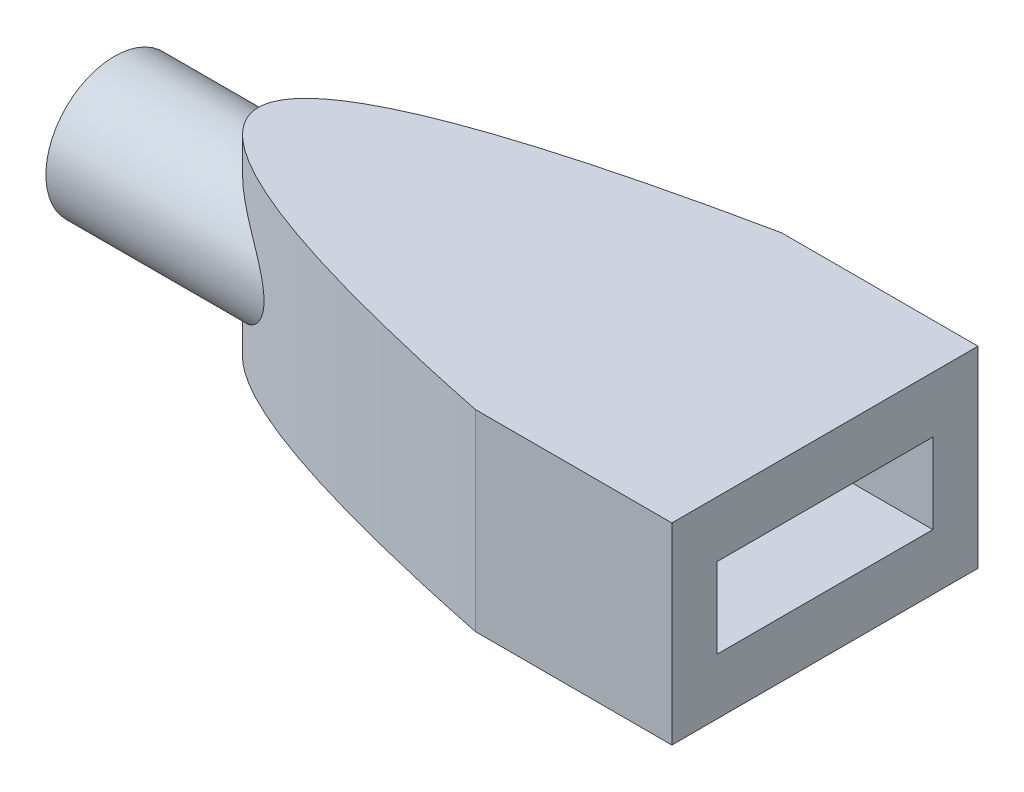
SolidWorks part; units mm, degrees
ref_plane "Front Plane" through (0, 0, 0) normal (0, 0, 1) x (1, 0, 0)
ref_plane "Top Plane" through (0, 0, 0) normal (0, 1, 0) x (1, 0, 0)
ref_plane "Right Plane" through (0, 0, 0) normal (1, 0, 0) x (0, 0, -1)
sketch "Sketch1" plane through (0, 0, 0) normal (0, 1, 0) x (1, 0, 0)
  line L1 (-5.461, -8.509) -> (5.461, -8.509)
  line L2 (-5.461, -8.509) -> (-5.461, 8.509)
  line L3 (-5.461, 8.509) -> (5.461, 8.509)
  line L4 (5.461, -8.509) -> (5.461, 8.509)
  line L5 (-5.461, -8.509) -> (5.461, 8.509) construction
  line L6 (-5.461, 8.509) -> (5.461, -8.509) construction
  point P0 (0, 0)
  dimension "D1" = 17.018
  dimension "D2" = 10.922
extrude "Boss-Extrude1" add sketch "Sketch1" along normal mid plane 10.6934
sketch "Sketch2" plane through (5.461, 0, 0) normal (1, 0, 0) x (0, 0, -1)
  line L1 (-6.0008, -2.2288) -> (6.0007, -2.2288)
  line L2 (-6.0008, -2.2288) -> (-6.0008, 2.2288)
  line L3 (-6.0008, 2.2288) -> (6.0007, 2.2288)
  line L4 (6.0007, -2.2288) -> (6.0007, 2.2288)
  line L5 (-6.0008, -2.2288) -> (6.0007, 2.2288) construction
  line L6 (-6.0008, 2.2288) -> (6.0007, -2.2288) construction
  point P0 (0, 0)
  dimension "D1" = 12.0015
  dimension "D2" = 4.4577
extrude "Cut-Extrude1" cut sketch "Sketch2" against normal blind 9.7536
sketch "Sketch3" plane through (0, 5.3467, 0) normal (0, 1, 0) x (1, 0, 0)
  line L0 (-5.461, 0) -> (-26.035, 0) construction
  line L1 (-5.461, 8.509) -> (-5.461, -8.509) construction
  line L6 (5.461, -8.509) -> (5.461, 8.509)
  line L7 (5.461, 8.509) -> (-5.461, 8.509)
  line L8 (-5.461, 8.509) -> (-5.461, -8.509)
  line L9 (-5.461, -8.509) -> (5.461, -8.509)
  line L12 (-5.461, 8.509) -> (-5.461, -8.509)
  spline S0 degree 2 poles (-5.461, 8.509) (-46.609, 0) (-5.461, -8.509) knots 0 0 0 1 1 1
  dimension "D1" = 20.574
  dimension "D2" = 0
extrude "Boss-Extrude2" add sketch "Sketch3" against normal up to surface (10.6934 mm away) up to face at (0, -5.3467, 0)
ref_plane "Plane1" through (-26.035, 0, 0) normal (1, 0, 0) x (0, 0, -1)
sketch "Sketch4" plane through (-26.035, 0, 0) normal (1, 0, 0) x (0, 0, -1)
  circle A0 centre (0, 0) radius 3.81
extrude "Boss-Extrude3" add sketch "Sketch4" along normal blind 9.7536 and the other way blind 8.001 contours A0
